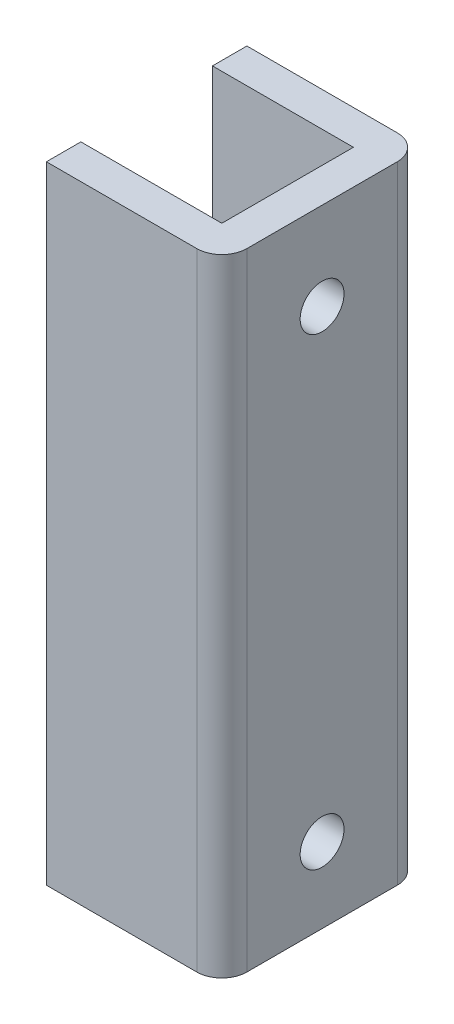
SolidWorks part; units mm, degrees
ref_plane "前视基准面" through (0, 0, 0) normal (0, 0, 1) x (1, 0, 0)
ref_plane "上视基准面" through (0, 0, 0) normal (0, 1, 0) x (1, 0, 0)
ref_plane "右视基准面" through (0, 0, 0) normal (1, 0, 0) x (0, 0, -1)
sketch "草图1" plane through (0, 0, 0) normal (0, 1, 0) x (1, 0, 0)
  line L0 (-8.9538, 10.5077) -> (-8.9538, -5.4923)
  line L1 (-8.9538, -5.4923) -> (3.0462, -5.4923)
  line L2 (-8.9538, 10.5077) -> (3.0462, 10.5077)
  line L3 (5.0462, 8.5077) -> (5.0462, -3.4923)
  arc A0 (3.0462, 10.5077) -> (5.0462, 8.5077) centre (3.0462, 8.5077) cw
  arc A1 (3.0462, -5.4923) -> (5.0462, -3.4923) centre (3.0462, -3.4923) ccw
  point P10 (5.0462, -5.4923)
  dimension "D3" = 2
  dimension "D4" = 2
  dimension "D1" = 16
  dimension "D2" = 14
extrude "凸台-拉伸1" add sketch "草图1" along normal blind 50
sketch "草图2" plane through (0, 50, 0) normal (0, 1, 0) x (1, 0, 0)
  line L12 (2.2962, 7.7577) -> (-6.2038, 7.7577)
  line L13 (-6.2038, 7.7577) -> (-6.2038, -2.7423)
  line L14 (-6.2038, -2.7423) -> (2.2962, -2.7423)
  line L15 (2.2962, -2.7423) -> (2.2962, 7.7577)
  line L16 (2.2962, 7.7577) -> (-6.2038, 7.7577)
  line L17 (-6.2038, 7.7577) -> (-6.2038, -2.7423)
  line L18 (-6.2038, -2.7423) -> (2.2962, -2.7423)
  line L19 (2.2962, -2.7423) -> (2.2962, 7.7577)
  dimension "D1" = 2.75
extrude "切除-拉伸1" cut sketch "草图2" against normal through all
sketch "草图3" plane through (0, 50, 0) normal (0, 1, 0) x (1, 0, 0)
  line L0 (-6.2038, 7.7577) -> (-8.9538, 7.7577)
  line L1 (-8.9538, 10.5077) -> (-8.9538, -5.4923) construction
  line L2 (-8.9538, 7.7577) -> (-8.9538, -2.7423)
  line L3 (-8.9538, -2.7423) -> (-6.2038, -2.7423)
  line L4 (-6.2038, -2.7423) -> (-6.2038, 7.7577)
extrude "切除-拉伸2" cut sketch "草图3" against normal through all
sketch "草图4" plane through (5.0462, 0, 0) normal (1, 0, 0) x (0, 0, -1)
  line L0 (-3.4923, 50) -> (-3.4923, 0) construction
  line L1 (-3.4923, 50) -> (8.5077, 50) construction
  circle A0 centre (2.5077, 43) radius 1.75
  circle A1 centre (2.5077, 6) radius 1.75
  dimension "D1" = 6
  dimension "D5" = 3.5
  dimension "D6" = 3.5
  dimension "D2" = 7
  dimension "D3" = 37
  dimension "D4" = 6
extrude "切除-拉伸3" cut sketch "草图4" against normal through all
